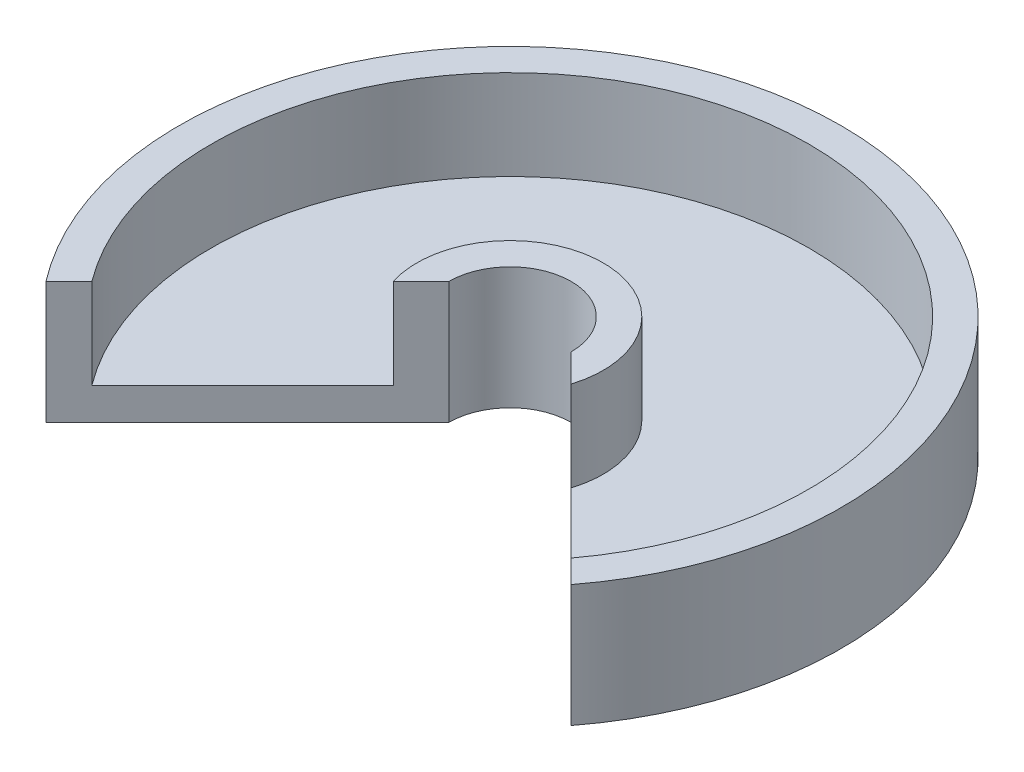
SolidWorks part; units mm, degrees
ref_plane "Alzado" through (0, 0, 0) normal (0, 0, 1) x (1, 0, 0)
ref_plane "Planta" through (0, 0, 0) normal (0, 1, 0) x (1, 0, 0)
ref_plane "Vista lateral" through (0, 0, 0) normal (1, 0, 0) x (0, 0, -1)
sketch "Croquis1" plane through (0, 0, 0) normal (0, 0, 1) x (1, 0, 0)
  line L0 (-16.0044, 9.1503) -> (-16.0044, -10.0705) construction
  line L1 (-17.9044, -1.5158) -> (-17.9044, 2.2842)
  line L3 (-26.3044, 2.2842) -> (-26.3044, -1.5158)
  line L4 (-26.3044, -1.5158) -> (-17.9044, -1.5158)
  line L5 (-26.3044, 2.2842) -> (-25.3044, 2.2842)
  line L6 (-25.3044, 2.2842) -> (-25.3044, -0.5158)
  line L7 (-25.3044, -0.5158) -> (-18.9044, -0.5158)
  line L8 (-18.9044, -0.5158) -> (-18.9044, 2.2842)
  line L9 (-18.9044, 2.2842) -> (-17.9044, 2.2842)
  dimension "D1" = 1.9
  dimension "D2" = 3.8
revolve "Revolución1" add sketch "Croquis1" angle 360 about L0
sketch "Croquis2" plane through (0, 2.2842, 0) normal (0, 1, 0) x (1, 0, 0)
  line L0 (-17.9044, 0) -> (-24.1754, -6.271)
  line L1 (-14.1044, 0) -> (-7.8334, -6.271)
  circle A2 centre (-16.0044, 0) radius 1.9 construction
  circle A3 centre (-16.0044, 0) radius 10.3 construction
  arc A4 (-14.1044, 0) -> (-17.9044, 0) centre (-16.0044, 0) cw
  arc A5 (-7.8334, -6.271) -> (-24.1754, -6.271) centre (-16.0044, 0) cw
extrude "Cortar-Extruir1" cut sketch "Croquis2" against normal blind 10
